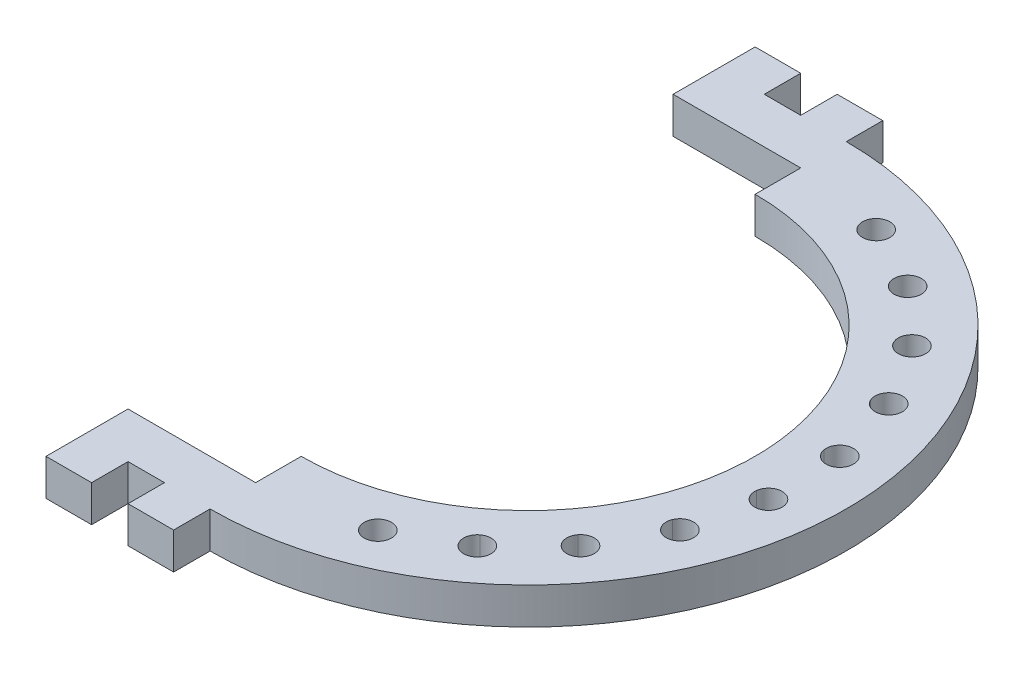
SolidWorks part; units mm, degrees
ref_plane "Front Plane" through (0, 0, 0) normal (0, 0, 1) x (1, 0, 0)
ref_plane "Top Plane" through (0, 0, 0) normal (0, 1, 0) x (1, 0, 0)
ref_plane "Right Plane" through (0, 0, 0) normal (1, 0, 0) x (0, 0, -1)
sketch "Sketch1" plane through (0, 0, 0) normal (0, 1, 0) x (1, 0, 0)
  line L0 (0, 34.9) -> (0, -34.9)
  arc A0 (0, -34.9) -> (0, 34.9) centre (0, 0) ccw
  arc A1 (0, -24.9) -> (0, 24.9) centre (0, 0) ccw
  point P4 (0, 0)
  dimension "D2" = 10
  dimension "D1" = 69.8
extrude "Boss-Extrude1" add sketch "Sketch1" along normal blind 4 contours A1 L0 A0
sketch "Sketch2" plane through (0, 4, 0) normal (0, 1, 0) x (1, 0, 0)
  line L0 (0, 29.9) -> (-14, 29.9)
  line L1 (0, 34.9) -> (0, 24.9) construction
  line L2 (-14, 29.9) -> (-14, 34.9)
  line L3 (-14, 34.9) -> (0, 34.9)
  line L4 (-14, 34.9) -> (-14, 38.9)
  line L5 (-14, 38.9) -> (-9, 38.9)
  line L6 (-9, 38.9) -> (-9, 34.9)
  line L7 (-5, 38.9) -> (0, 38.9)
  line L8 (0, 38.9) -> (0, 34.9)
  line L9 (-5, 34.9) -> (-5, 38.9)
  line L10 (0, 0) -> (34.9, 0) construction
  line L11 (-5, -34.9) -> (-5, -38.9)
  line L12 (0, -38.9) -> (0, -34.9)
  line L13 (-5, -38.9) -> (0, -38.9)
  line L14 (-9, -38.9) -> (-9, -34.9)
  line L15 (-14, -38.9) -> (-9, -38.9)
  line L16 (-14, -34.9) -> (-14, -38.9)
  line L17 (-14, -34.9) -> (0, -34.9)
  line L18 (-14, -29.9) -> (-14, -34.9)
  line L19 (0, -29.9) -> (-14, -29.9)
  arc A0 (0, -34.9) -> (0, 34.9) centre (0, 0) ccw construction
  line M7 (0, -24.9) -> (0, -34.9)
  line M9 (0, 34.9) -> (0, 24.9)
  dimension "D1" = 14
  dimension "D2" = 4
  dimension "D3" = 5
extrude "Boss-Extrude2" add sketch "Sketch2" against normal through all contours L6 L5 L4 L3 | L3 L2 L0 M9 | L9 L3 L8 L7 | L19 L18 L17 M7 | L17 L16 L15 L14 | L17 L11 L13 L12
sketch "Sketch3" plane through (0, 4, 0) normal (0, 1, 0) x (1, 0, 0)
  line L0 (0, 29.9) -> (0, 24.9) construction
  line L1 (0, 0) -> (10, 28.1782) construction
  line L2 (0, 0) -> (17.1136, 24.518) construction
  circle A0 centre (0, 0) radius 29.9 construction
  circle A2 centre (10, 28.1782) radius 1.5
  circle A3 centre (17.1136, 24.518) radius 1.5
  arc A4 (0, -24.9) -> (0, 24.9) centre (0, 0) ccw construction
  dimension "D1" = 5
  dimension "D2" = 3
  dimension "D4" = 8
  dimension "D3" = 10
  dimension "D5" = 15.376
extrude "Cut-Extrude1" cut sketch "Sketch3" against normal through all
pattern_circular "CirPattern2" count 9 every 15.38 about axis through (0, 0, 0) along (0, 1, 0) of "Cut-Extrude1"
sketch "Sketch4" plane through (0, 4, 0) normal (0, 1, 0) x (1, 0, 0)
  line L0 (0, 0) -> (29.5367, 4.647) construction
  arc A0 (10, 28.1782) -> (11.2225, -27.714) centre (0, 0) cw construction
  arc A1 (11.7855, -29.1043) -> (10.5017, 29.5918) centre (0, 0) ccw
  arc A2 (10.6595, -26.3237) -> (9.4983, 26.7646) centre (0, 0) ccw
  arc A3 (10.6595, -26.3237) -> (11.7855, -29.1043) centre (11.2225, -27.714) ccw
  arc A4 (10.5017, 29.5918) -> (9.4983, 26.7646) centre (10, 28.1782) ccw
  point P3 (29.8929, 0.6538)
  dimension "D1" = 1.5
extrude "Cut-Extrude2" [suppressed] cut sketch "Sketch4" against normal through all
